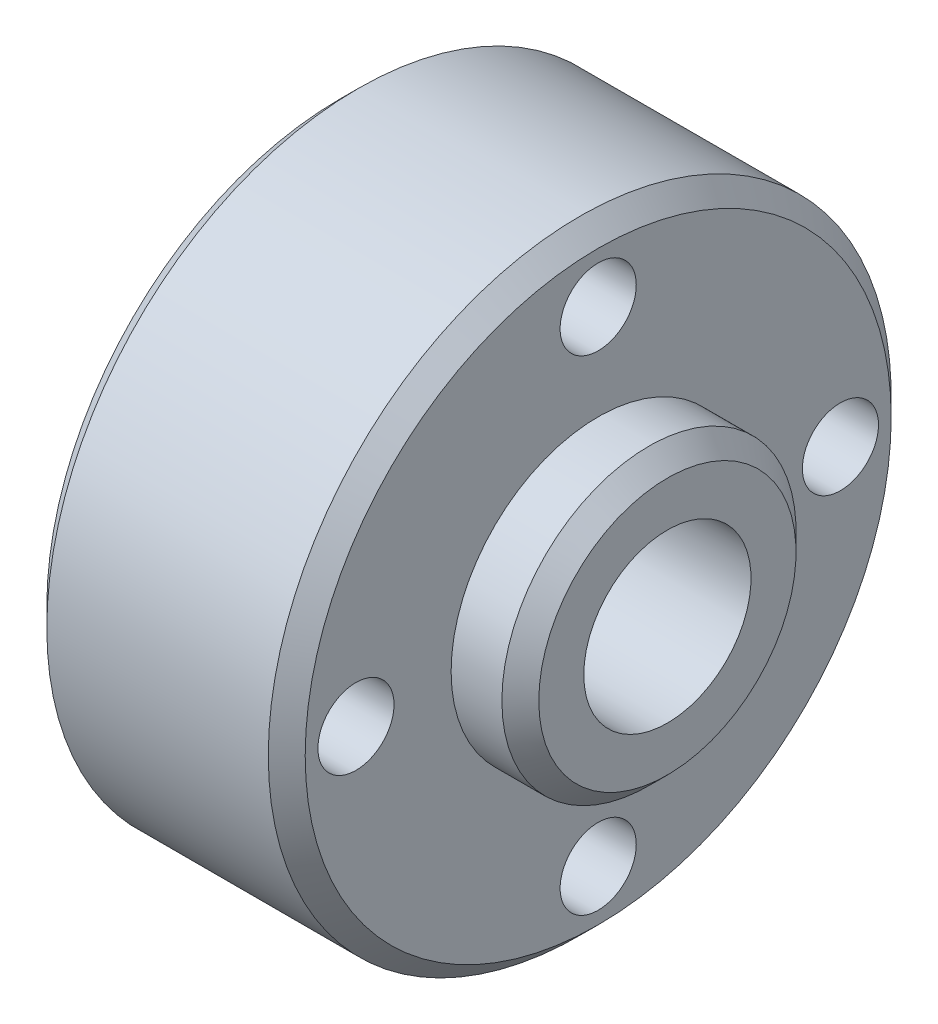
SolidWorks part; units mm, degrees
material "PLA"
ref_plane "前视基准面" through (0, 0, 0) normal (0, 0, 1) x (1, 0, 0)
ref_plane "上视基准面" through (0, 0, 0) normal (0, 1, 0) x (1, 0, 0)
ref_plane "右视基准面" through (0, 0, 0) normal (1, 0, 0) x (0, 0, -1)
sketch "草图1" plane through (0, 0, 0) normal (0, 0, 1) x (1, 0, 0)
  line L0 (0, 0) -> (25.3616, 0) construction
  line L1 (0, 0) -> (0, 13.5) construction
  line L2 (0, 13.5) -> (11.2, 13.5)
  line L3 (11.2, 13.5) -> (11.2, 6.375)
  line L4 (11.2, 6.375) -> (14.2, 6.375)
  line L5 (14.2, 6.375) -> (14.2, 3.625)
  line L6 (14.2, 3.625) -> (7, 3.625)
  line L7 (7, 3.625) -> (7, 7.625)
  line L8 (7, 7.625) -> (0, 7.625)
  line L9 (0, 7.625) -> (0, 13.5)
  dimension "D1" = 15.25
  dimension "D2" = 27
  dimension "D3" = 12.75
  dimension "D4" = 4
  dimension "D5" = 7
  dimension "D6" = 11.2
  dimension "D7" = 3
revolve "旋转1" add sketch "草图1" angle 360 about L0
sketch "草图2" plane through (11.2, 0, 0) normal (1, 0, 0) x (0, 0, -1)
  circle A0 centre (0, 0) radius 10.5 construction
  circle A1 centre (0, 10.5) radius 1.65
  circle A2 centre (10.5, 0) radius 1.65
  circle A3 centre (0, -10.5) radius 1.65
  circle A4 centre (-10.5, 0) radius 1.65
  dimension "D1" = 21
  dimension "D2" = 3.3
extrude "切除-拉伸1" cut sketch "草图2" against normal through all
chamfer "倒角1" distance 0.8 angle 45 4 edges at (11.2, 0, 13.5) (0, 0, 13.5) (14.2, 0, 6.375) (0, 0, 7.625)
